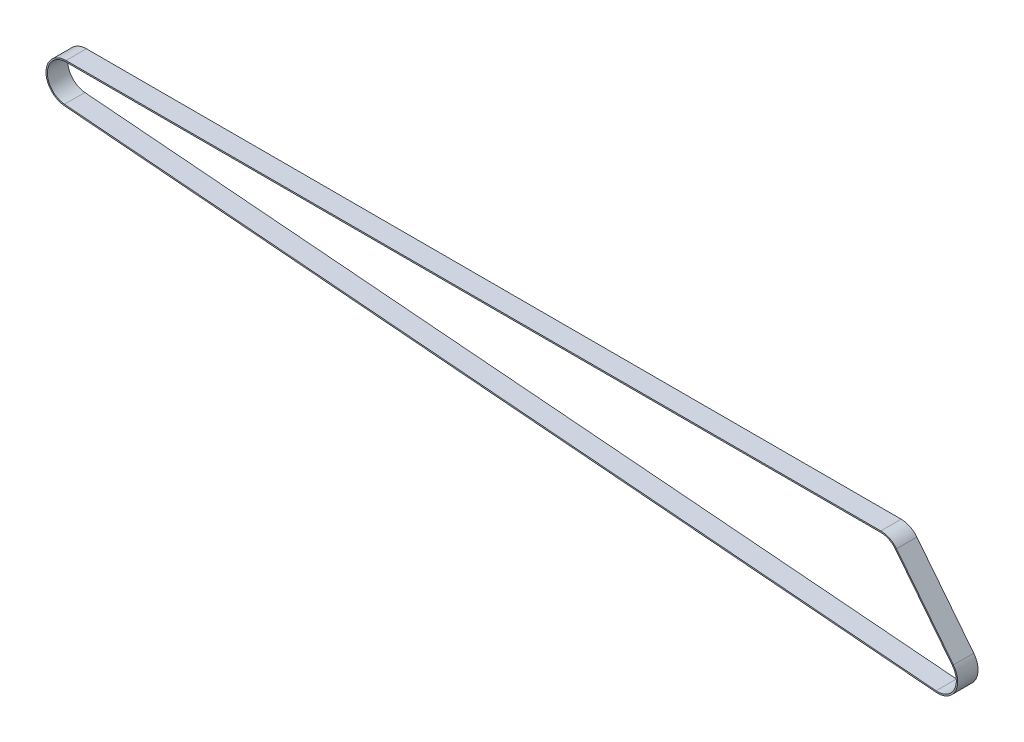
SolidWorks part; units mm, degrees
ref_plane "Ebene vorne" through (0, 0, 0) normal (0, 0, 1) x (1, 0, 0)
ref_plane "Ebene oben" through (0, 0, 0) normal (0, 1, 0) x (1, 0, 0)
ref_plane "Ebene rechts" through (0, 0, 0) normal (1, 0, 0) x (0, 0, -1)
sketch "Skizze1" plane through (0, 0, 0) normal (0, 0, 1) x (1, 0, 0)
  line L0 (-240, 0) -> (240, 0) construction
  line L1 (240, 0) -> (240, -42.5) construction
  line L2 (240, -42.5) -> (273.5, -42.5) construction
  line L3 (-240, 11) -> (240, 11)
  line L4 (248.6389, 6.8095) -> (282.1389, -35.6905)
  line L5 (-240.9073, -10.9625) -> (272.5927, -53.4625)
  circle A0 centre (273.5, -42.5) radius 11 construction
  circle A1 centre (240, 0) radius 11 construction
  circle A2 centre (-240, 0) radius 11 construction
  arc A3 (282.1389, -35.6905) -> (272.5927, -53.4625) centre (273.5, -42.5) cw
  arc A4 (240, 11) -> (248.6389, 6.8095) centre (240, 0) cw
  arc A5 (-240.9073, -10.9625) -> (-240, 11) centre (-240, 0) cw
  dimension "D4" = 22
  dimension "D1" = 480
  dimension "D2" = 42.5
  dimension "D3" = 33.5
extrude "Linear-Austragen-Dünn1" add sketch "Skizze1" along normal mid plane 12 thin thin type one direction wall 0.8
sketch "Skizze2" plane through (0, 0, 0) normal (0, 0, 1) x (1, 0, 0)
  line L0 (-240, 11) -> (240, 11) construction
  line L1 (-80, 9) -> (-73.6173, 9)
  line L2 (-73.6173, 9) -> (-63.5107, 6.4895)
  line L3 (-80, 11) -> (-78.5811, 11.8468)
  line L4 (-78.5811, 11.8468) -> (-65.2454, 12.7313)
  circle A0 centre (-80, 10) radius 1 construction
  arc A1 (-80, 9) -> (-80, 11) centre (-80, 10) cw
  dimension "D2" = 2
  dimension "D1" = 160
extrude "Linear-Austragen-Dünn2" [suppressed] add sketch "Skizze2" along normal mid plane 12 thin
